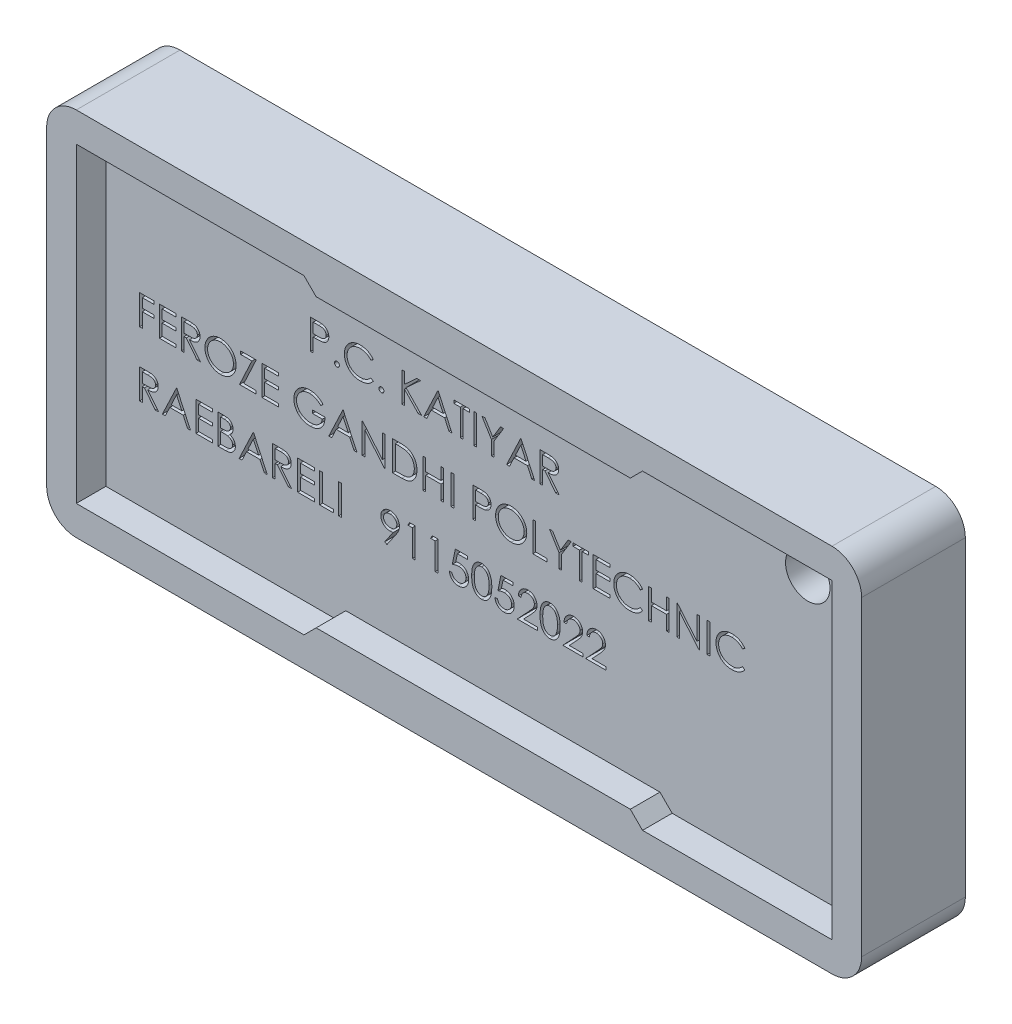
SolidWorks part; units mm, degrees
ref_plane "Front Plane" through (0, 0, 0) normal (0, 0, 1) x (1, 0, 0)
ref_plane "Top Plane" through (0, 0, 0) normal (0, 1, 0) x (1, 0, 0)
ref_plane "Right Plane" through (0, 0, 0) normal (1, 0, 0) x (0, 0, -1)
sketch "Sketch1" plane through (0, 0, 0) normal (0, 0, 1) x (1, 0, 0)
  line L1 (-25.5, -12.5) -> (25.5, -12.5)
  line L2 (-27.5, -10.5) -> (-27.5, 10.5)
  line L3 (-25.5, 12.5) -> (25.5, 12.5)
  line L4 (27.5, -10.5) -> (27.5, 10.5)
  line L5 (-27.5, -12.5) -> (27.5, 12.5) construction
  line L6 (-27.5, 12.5) -> (27.5, -12.5) construction
  arc A0 (-25.5, -12.5) -> (-27.5, -10.5) centre (-25.5, -10.5) cw
  arc A1 (27.5, -10.5) -> (25.5, -12.5) centre (25.5, -10.5) cw
  arc A2 (27.5, 10.5) -> (25.5, 12.5) centre (25.5, 10.5) ccw
  arc A3 (-25.5, 12.5) -> (-27.5, 10.5) centre (-25.5, 10.5) ccw
  point P0 (0, 0)
  dimension "D3" = 2
  dimension "D1" = 55
  dimension "D2" = 25
extrude "Boss-Extrude1" add sketch "Sketch1" along normal blind 7
sketch "Sketch2" plane through (0, 0, 0) normal (0, 0, -1) x (-1, 0, 0)
  line L0 (-27.5, -10.5) -> (-27.5, 10.5) construction
  line L1 (-25.5, -10.5) -> (-11.552, -10.5)
  line L2 (-25.5, -10.5) -> (-25.5, 10.5)
  line L3 (-25.5, 10.5) -> (-11.552, 10.5)
  line L4 (25.5, -10.5) -> (25.5, 10.5)
  line L5 (-25.5, -10.5) -> (-23.5, -9.6765) construction
  line L6 (-25.5, 10.5) -> (-23.5, 9.6765) construction
  line L7 (-25.5, 12.5) -> (25.5, 12.5) construction
  line L8 (-11.552, 10.5) -> (-10.7284, 9.6765)
  line L13 (-23.5, -9.6765) -> (0, 0) construction
  line L14 (10.0955, 10.5) -> (25.5, 10.5)
  line L15 (-11.552, 10.5) -> (-25.5, 10.5)
  line L16 (9.272, 9.6765) -> (10.0955, 10.5)
  line L17 (-11.552, -10.5) -> (-10.7284, -9.6765)
  line L18 (10.0955, -10.5) -> (25.5, -10.5)
  line L19 (9.272, -9.6765) -> (10.0955, -10.5)
  line L20 (-11.552, -10.5) -> (-25.5, -10.5)
  line L22 (10.0955, -10.5) -> (9.272, -9.6765)
  line L23 (25.5, -10.5) -> (10.0955, -10.5)
  line L24 (25.5, -10.5) -> (25.5, 10.5)
  line L25 (25.5, 10.5) -> (10.0955, 10.5)
  line L26 (-25.5, -10.5) -> (-25.5, 10.5)
  line L27 (23.5, -9.6765) -> (-25.5, 10.5) construction
  line L28 (25.5, 10.5) -> (-25.5, -10.5) construction
  line L29 (9.272, -9.6765) -> (-10.7284, -9.6765)
  line L31 (9.272, 9.6765) -> (-10.7284, 9.6765)
  line L33 (23.5, -9.6765) -> (-23.5, 9.6765) construction
  line L34 (23.5, 9.6765) -> (-23.5, -9.6765) construction
  line L35 (-10.7284, -9.6765) -> (-11.552, -10.5)
  line L36 (10.0955, 10.5) -> (9.272, 9.6765)
  line L37 (-10.7284, 9.6765) -> (-11.552, 10.5)
  point P0 (0, 0)
  point P10 (0, 0)
  dimension "D1" = 2
  dimension "D2" = 2
extrude "Cut-Extrude1" cut sketch "Sketch2" against normal blind 2 contours L16 L31 L8 L3 L2 L1 L17 L29 L19 L18 L4 L14
sketch "Sketch3" plane through (0, 0, 7) normal (0, 0, 1) x (1, 0, 0)
  line L0 (-27.5, 10.5) -> (-27.5, -10.5) construction
  line L1 (-25.5, -10.5) -> (-10.1359, -10.5)
  line L2 (-25.5, -10.5) -> (-25.5, 10.5)
  line L3 (-25.5, 10.5) -> (-10.1359, 10.5)
  line L4 (25.5, -10.5) -> (25.5, 10.5)
  line L5 (-25.5, -10.5) -> (-23.5, -9.6765) construction
  line L6 (-25.5, 10.5) -> (-23.5, 9.6765) construction
  line L7 (25.5, 12.5) -> (-25.5, 12.5) construction
  line L8 (-10.1359, 10.5) -> (-9.3123, 9.6765)
  line L9 (-9.3123, -9.6765) -> (11.8893, -9.6765)
  line L13 (-23.5, -9.6765) -> (0, 0) construction
  line L14 (-23.5, 9.6765) -> (0, 0) construction
  line L17 (12.7129, 10.5) -> (11.8893, 9.6765)
  line L18 (12.7129, 10.5) -> (25.5, 10.5)
  line L19 (-10.1359, -10.5) -> (-9.3123, -9.6765)
  line L20 (-9.3123, -9.6765) -> (11.8893, -9.6765)
  line L21 (11.8893, -9.6765) -> (12.7129, -10.5)
  line L22 (-9.3123, 9.6765) -> (11.8893, 9.6765)
  line L23 (0, 0) -> (25.5, -10.5) construction
  line L24 (0, 0) -> (25.5, 10.5) construction
  line L25 (12.7129, -10.5) -> (25.5, -10.5)
  point P0 (0, 0)
  point P10 (0, 0)
  dimension "D1" = 2
  dimension "D2" = 2
extrude "Cut-Extrude2" cut sketch "Sketch3" against normal blind 2 contours L21 L25 L4 L18 L17 L22 L8 L3 L2 L1 L19 L9
sketch "Sketch4" plane through (0, 0, 5) normal (0, 0, 1) x (1, 0, 0)
  text T0 "               P.C. KATIYAR\r\nFEROZE GANDHI POLYTECHNIC\r\nRAEBARELI   9115052022\r\n" font "Century Gothic" height 2
extrude "Cut-Extrude7" cut sketch "Sketch4" against normal blind 2
sketch "Sketch5" plane through (0, 0, 5) normal (0, 0, 1) x (1, 0, 0)
  circle A0 centre (21.8632, 7.9753) radius 1.5
extrude "Cut-Extrude8" cut sketch "Sketch5" against normal blind 3
